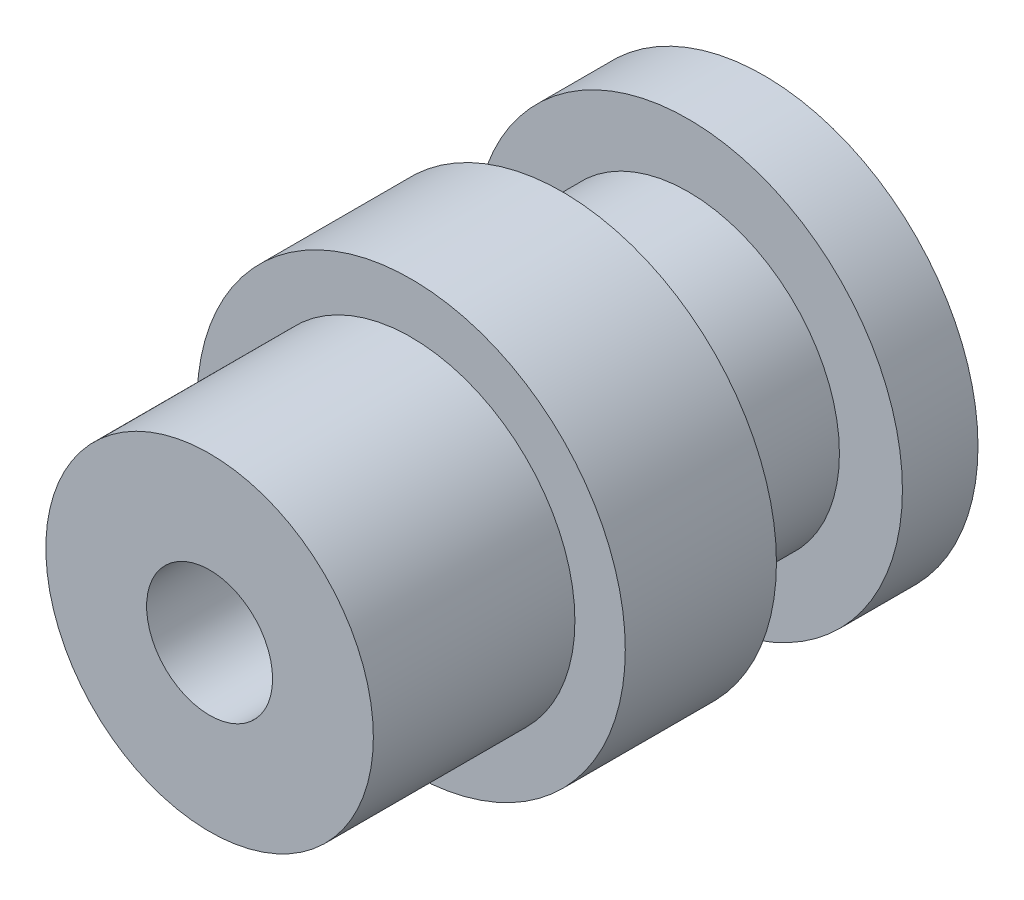
SolidWorks part; units mm, degrees
ref_plane "Front Plane" through (0, 0, 0) normal (0, 0, 1) x (1, 0, 0)
ref_plane "Top Plane" through (0, 0, 0) normal (0, 1, 0) x (1, 0, 0)
ref_plane "Right Plane" through (0, 0, 0) normal (1, 0, 0) x (0, 0, -1)
other "Configuration Table"
sketch "Sketch1" plane through (0, 0, 0) normal (0, 0, 1) x (1, 0, 0)
  circle A0 centre (0, 0) radius 6
  dimension "D1" = 12
extrude "Thread" add sketch "Sketch1" along normal blind 5 from offset 5
sketch "Sketch2" plane through (0, 0, 0) normal (0, 0, 1) x (1, 0, 0)
  circle A0 centre (0, 0) radius 8.5
  dimension "D1" = 17
extrude "Lock_Nut" add sketch "Sketch2" along normal blind 3 from offset 8
sketch "Sketch3" plane through (0, 0, 0) normal (0, 0, 1) x (1, 0, 0)
  circle A0 centre (0, 0) radius 8.5
  dimension "D1" = 17
extrude "Body" add sketch "Sketch3" along normal blind 6
sketch "Sketch4" plane through (0, 0, 0) normal (0, 0, 1) x (1, 0, 0)
  circle A0 centre (0, 0) radius 6.5
  dimension "D1" = 13
extrude "Dome" add sketch "Sketch4" along normal blind 8 from offset 6
sketch "Sketch5" plane through (0, 0, 0) normal (0, 0, 1) x (1, 0, 0)
  circle A0 centre (0, 0) radius 2.5
  dimension "D1" = 5
extrude "Cable_Hole" cut sketch "Sketch5" along normal through all and the other way through all
equation "\"Jar_OD\"= 90  'ASSUMED - Part G fallback - jar outer diameter"
equation "\"Jar_H\"= 120  'ASSUMED - Part G fallback - jar height"
equation "\"Pump_L\"= 45  'ASSUMED - Part G fallback"
equation "\"Pump_W\"= 24  'ASSUMED - Part G fallback"
equation "\"Pump_H\"= 33  'ASSUMED - Part G fallback"
equation "\"Pump_Outlet_OD\"= 7.5  'ASSUMED - Part G fallback"
equation "\"Tube_OD\"= 8  'ASSUMED - Part G fallback"
equation "\"Tube_ID\"= 6  'ASSUMED - Part G fallback"
equation "\"TDS_Body_Dia\"= 12  'ASSUMED - Part G fallback"
equation "\"TDS_Wet_Len\"= 45  'ASSUMED - Part G fallback - length in water"
equation "\"DS_Tube_Dia\"= 6  'ASSUMED - Part G fallback"
equation "\"DS_Tube_Len\"= 50  'ASSUMED - Part G fallback"
equation "\"ORP_Body_Dia\"= 12  'ASSUMED - Part G fallback"
equation "\"ORP_Body_Len\"= 150  'ASSUMED - Part G fallback"
equation "\"ORP_Cap_Dia\"= 16  'ASSUMED - Part G fallback"
equation "\"Turb_W\"= 33  'ASSUMED - Part G fallback - head width"
equation "\"Turb_D\"= 28  'ASSUMED - Part G fallback - head depth"
equation "\"Turb_H\"= 30  'ASSUMED - Part G fallback - head height"
equation "\"Turb_Slot_W\"= 10  'ASSUMED - Part G fallback - slot width"
equation "\"Flow_L\"= 62  'ASSUMED - Part G fallback YF-S201"
equation "\"Flow_W\"= 36  'ASSUMED - Part G fallback"
equation "\"Flow_H\"= 35  'ASSUMED - Part G fallback"
equation "\"Thread_G12_OD\"= 20.955  'ASSUMED - Part G fallback thread G1/2 (major diameter)"
equation "\"Valve_L\"= 75  'ASSUMED - Part G fallback"
equation "\"Valve_W\"= 45  'ASSUMED - Part G fallback"
equation "\"Valve_H\"= 60  'ASSUMED - Part G fallback"
equation "\"Tee_L\"= 40  'ASSUMED - Part G fallback - overall length"
equation "\"Tee_Branch_L\"= 25  'ASSUMED - Part G fallback"
equation "\"Tee_OD\"= 12  'ASSUMED - Part G fallback"
equation "\"LED_Board_L\"= 20  'ASSUMED - Part G fallback"
equation "\"LED_Board_W\"= 20  'ASSUMED - Part G fallback - LED at centre"
equation "\"GUVA_L\"= 20  'ASSUMED - Part G fallback"
equation "\"GUVA_W\"= 12  'ASSUMED - Part G fallback - sensor at centre"
equation "\"Reed_L\"= 27  'ASSUMED - Part G fallback MC-38 half"
equation "\"Reed_W\"= 14  'ASSUMED - Part G fallback"
equation "\"Reed_H\"= 8  'ASSUMED - Part G fallback"
equation "\"ESP_L\"= 51  'ASSUMED - Part G fallback"
equation "\"ESP_W\"= 28  'ASSUMED - Part G fallback"
equation "\"TFT_L\"= 58  'ASSUMED - Part G fallback - board"
equation "\"TFT_W\"= 35  'ASSUMED - Part G fallback - board"
equation "\"TFT_Win_L\"= 35  'ASSUMED - Part G fallback - visible window"
equation "\"TFT_Win_W\"= 28  'ASSUMED - Part G fallback - visible window"
equation "\"Relay_L\"= 50  'ASSUMED - Part G fallback"
equation "\"Relay_W\"= 26  'ASSUMED - Part G fallback"
equation "\"Relay_H\"= 19  'ASSUMED - Part G fallback"
equation "\"Mosfet_L\"= 34  'ASSUMED - Part G fallback"
equation "\"Mosfet_W\"= 17  'ASSUMED - Part G fallback"
equation "\"Mosfet_H\"= 12  'ASSUMED - Part G fallback"
equation "\"TDS_Board_L\"= 42  'ASSUMED - Part G fallback"
equation "\"TDS_Board_W\"= 32  'ASSUMED - Part G fallback"
equation "\"Turb_Board_L\"= 38  'ASSUMED - Part G fallback"
equation "\"Turb_Board_W\"= 28  'ASSUMED - Part G fallback"
equation "\"BNC_Thread_Dia\"= 9.5  'ASSUMED - Part G fallback"
equation "\"Plate_L\"= 420  'ASSUMED - Part G fallback"
equation "\"Plate_W\"= 297  'ASSUMED - Part G fallback"
equation "\"Plate_T\"= 6  'ASSUMED - Part G fallback"
equation "\"Booster_L\"= 150  'ASSUMED - Part G fallback - booster pump"
equation "\"Booster_W\"= 95  'ASSUMED - Part G fallback"
equation "\"Booster_H\"= 100  'ASSUMED - Part G fallback"
equation "\"PTube_OD\"= 6.35  'ASSUMED - Part G fallback - product tube 1/4 inch"
equation "\"Qz_Out\"= 12  'ASSUMED - Part G fallback - quartz channel outside square"
equation "\"Qz_Path\"= 10  'ASSUMED - Part G fallback - quartz channel inside light path"
equation "\"Qz_L\"= 40  'ASSUMED - Part G fallback - quartz channel length"
equation "\"LED860_Dia\"= 5  'ASSUMED - Part G fallback - 860 nm LED"
equation "\"BPW_L\"= 5.4  'ASSUMED - Part G fallback - BPW34"
equation "\"BPW_W\"= 4.3  'ASSUMED - Part G fallback - BPW34"
equation "\"Cart_Dia\"= 50  'ASSUMED - Part G fallback - sediment and pre-carbon cartridges"
equation "\"Cart_L\"= 255  'ASSUMED - Part G fallback"
equation "\"UF_Dia\"= 50  'ASSUMED - Part G fallback - UF cartridge"
equation "\"UF_L\"= 260  'ASSUMED - Part G fallback"
equation "\"RO_Dia\"= 62  'ASSUMED - Part G fallback - RO membrane housing"
equation "\"RO_L\"= 300  'ASSUMED - Part G fallback"
equation "\"UVC_Dia\"= 40  'ASSUMED - Part G fallback - UV-C chamber"
equation "\"UVC_L\"= 300  'ASSUMED - Part G fallback"
equation "\"Tank_W\"= 260  'ASSUMED - Part G fallback - storage tank"
equation "\"Tank_D\"= 160  'ASSUMED - Part G fallback"
equation "\"Tank_H\"= 300  'ASSUMED - Part G fallback"
equation "\"Cab_W\"= 400  'ASSUMED - Part G fallback - purifier cabinet"
equation "\"Cab_D\"= 270  'ASSUMED - Part G fallback"
equation "\"Cab_H\"= 560  'ASSUMED - Part G fallback"
equation "\"ORP_Board_L\"= 40  'ASSUMED - Part G fallback - ORP buffer board"
equation "\"ORP_Board_W\"= 30  'ASSUMED - Part G fallback"
equation "\"Opt_Board_L\"= 50  'ASSUMED - Part G fallback - optical front-end board"
equation "\"Opt_Board_W\"= 40  'ASSUMED - Part G fallback"
equation "\"Buck_L\"= 43  'ASSUMED - Part G fallback - 12 V to 5 V buck module"
equation "\"Buck_W\"= 21  'ASSUMED - Part G fallback"
equation "\"Buck_H\"= 14  'ASSUMED - Part G fallback"
equation "\"BB_L\"= 165  'ASSUMED - Part G fallback - breadboard (As_Built_R3 only)"
equation "\"BB_W\"= 55  'ASSUMED - Part G fallback"
equation "\"BB_H\"= 10  'ASSUMED - Part G fallback"
equation "\"Cuv_W\"= 12.5  'ASSUMED - old R3 cuvette (station suppressed in SS4)"
equation "\"Cuv_D\"= 12.5  'ASSUMED - old R3 cuvette (station suppressed in SS4)"
equation "\"Cuv_H\"= 45  'ASSUMED - old R3 cuvette (station suppressed in SS4)"
equation "\"Probe_Clr\"= 0.3  'DESIGN VALUE - Part C rule 3 - printed probe hole = diameter + 0.3"
equation "\"Label_H\"= 0.6  'DESIGN VALUE - Part D - raised label height"
